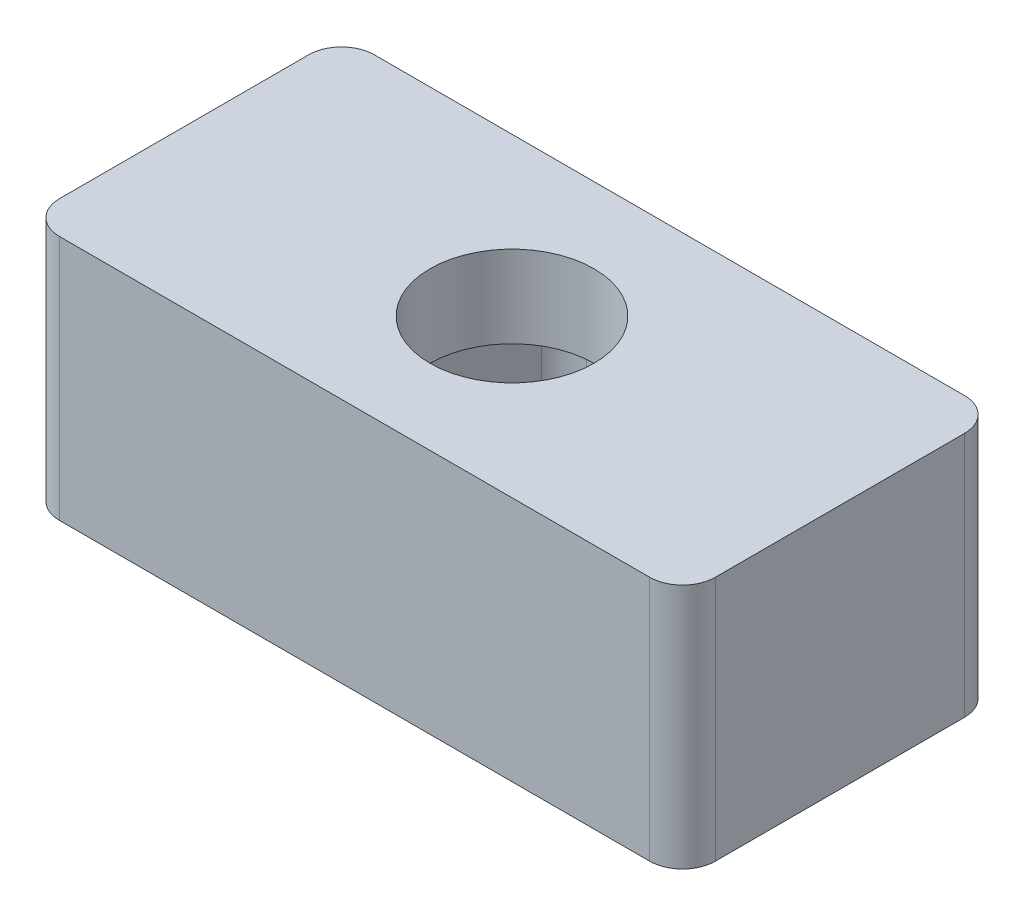
SolidWorks part; units mm, degrees
ref_plane "Front Plane" through (0, 0, 0) normal (0, 0, 1) x (1, 0, 0)
ref_plane "Top Plane" through (0, 0, 0) normal (0, 1, 0) x (1, 0, 0)
ref_plane "Right Plane" through (0, 0, 0) normal (1, 0, 0) x (0, 0, -1)
sketch "Sketch1" plane through (0, 0, 0) normal (0, 1, 0) x (1, 0, 0)
  line L1 (-10, 4.8) -> (10, 4.8)
  line L2 (-10, 4.8) -> (-10, -4.8)
  line L3 (-10, -4.8) -> (10, -4.8)
  line L4 (10, 4.8) -> (10, -4.8)
  line L5 (-10, 4.8) -> (10, -4.8) construction
  line L6 (-10, -4.8) -> (10, 4.8) construction
  line L7 (4.6188, 0) -> (2.3094, 4)
  line L8 (2.3094, 4) -> (-2.3094, 4)
  line L9 (-2.3094, 4) -> (-4.6188, 0)
  line L10 (-4.6188, 0) -> (-2.3094, -4)
  line L11 (-2.3094, -4) -> (2.3094, -4)
  line L12 (2.3094, -4) -> (4.6188, 0)
  circle A0 centre (0, 0) radius 4 construction
  point P0 (0, 0)
  dimension "D1" = 8
  dimension "D2" = 9.6
  dimension "D3" = 20
extrude "Boss-Extrude1" add sketch "Sketch1" along normal blind 5
sketch "Sketch2" plane through (0, 5, 0) normal (0, 1, 0) x (1, 0, 0)
  line L1 (-10, 4.8) -> (10, 4.8)
  line L2 (-10, 4.8) -> (-10, -4.8)
  line L3 (-10, -4.8) -> (10, -4.8)
  line L4 (10, 4.8) -> (10, -4.8)
  circle A0 centre (0, 0) radius 2.5
  dimension "D1" = 5
extrude "Boss-Extrude2" add sketch "Sketch2" along normal blind 2.5
fillet "Fillet1" radius 1 10 edges at (2.3094, 2.5, 4) (-2.3094, 2.5, 4) (-4.6188, 2.5, 0) (-2.3094, 2.5, -4) (2.3094, 2.5, -4) (4.6188, 2.5, 0) (-10, 3.75, -4.8) (10, 3.75, -4.8) (10, 3.75, 4.8) (-10, 3.75, 4.8)
